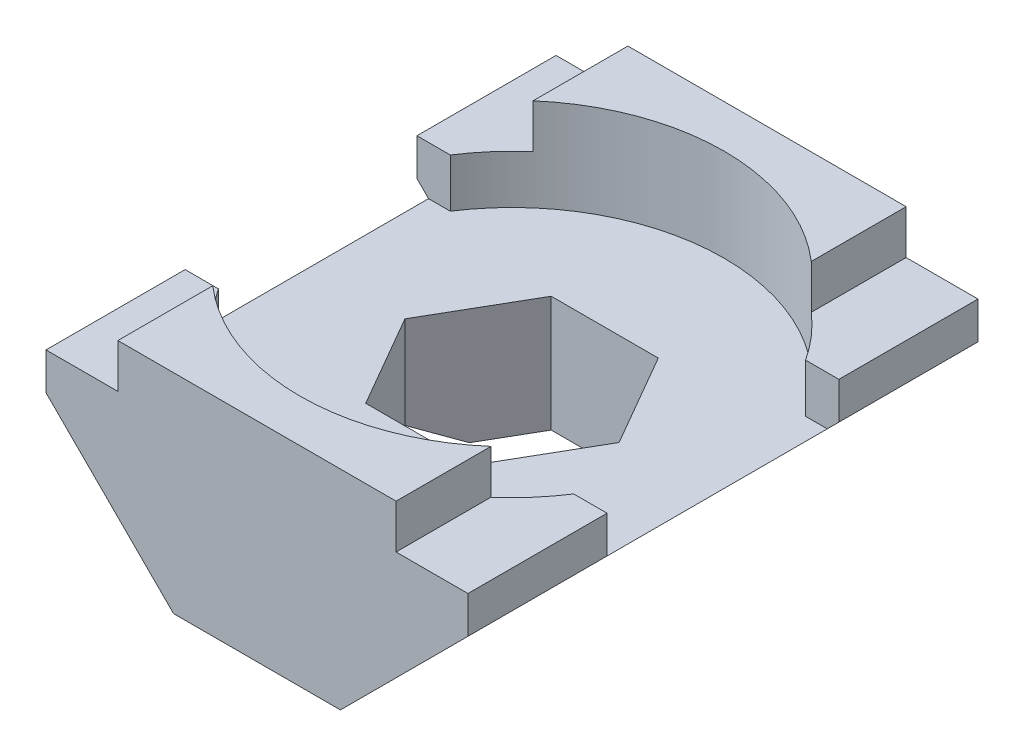
SolidWorks part; units mm, degrees
ref_plane "Front Plane" through (0, 0, 0) normal (0, 0, 1) x (1, 0, 0)
ref_plane "Top Plane" through (0, 0, 0) normal (0, 1, 0) x (1, 0, 0)
ref_plane "Right Plane" through (0, 0, 0) normal (1, 0, 0) x (0, 0, -1)
sketch "Sketch1" plane through (0, 0, 0) normal (0, 0, 1) x (1, 0, 0)
  line L0 (0, 0) -> (0, 5972.9771) construction
  line L1 (0, 0) -> (-5972.9771, 0) construction
  line L2 (0, 0) -> (0, 0.95)
  line L3 (0, 0.95) -> (6, 0.95)
  line L4 (6, 0.95) -> (6, 0)
  line L5 (6, 0) -> (7.55, 0)
  line L6 (7.55, 0) -> (7.55, -0.8)
  line L7 (7.55, -0.8) -> (4.8, -3.55)
  line L8 (4.8, -3.55) -> (1.2, -3.55)
  line L9 (1.2, -3.55) -> (-1.55, -0.8)
  line L10 (-1.55, -0.8) -> (-1.55, 0)
  line L11 (-1.55, 0) -> (0, 0)
  dimension "D1" = 0.95
  dimension "D2" = 1.55
  dimension "D3" = 1.55
  dimension "D4" = 6
  dimension "D5" = 0.8
  dimension "D6" = 0.8
  dimension "D7" = 135
  dimension "D8" = 135
  dimension "D9" = 4.5
extrude "Boss-Extrude1" add sketch "Sketch1" along normal blind 16
sketch "Sketch2" plane through (0, 0.95, 0) normal (0, 1, 0) x (1, 0, 0)
  line L0 (0, -8) -> (6, -8) construction
  line L1 (0, -16) -> (0, 0) construction
  line L2 (6, -16) -> (6, 0) construction
  circle A0 centre (3, -8) radius 4.575
  dimension "D1" = 9.15
extrude "Cut-Extrude1" cut sketch "Sketch2" against normal blind 2
sketch "Sketch3" plane through (0, -1.05, 0) normal (0, 1, 0) x (1, 0, 0)
  line L0 (3, -8) -> (5.3094, -8) construction
  line L1 (5.3094, -8) -> (4.1547, -6)
  line L2 (4.1547, -6) -> (1.8453, -6)
  line L3 (1.8453, -6) -> (0.6906, -8)
  line L4 (0.6906, -8) -> (1.8453, -10)
  line L5 (1.8453, -10) -> (4.1547, -10)
  line L6 (4.1547, -10) -> (5.3094, -8)
  circle A0 centre (3, -8) radius 2 construction
  dimension "D1" = 4
extrude "Cut-Extrude2" cut sketch "Sketch3" against normal through all
sketch "Sketch5" plane through (0, -1.05, 0) normal (0, 1, 0) x (1, 0, 0)
  line L0 (-1.55, -7.5224) -> (-1.55, 0) construction
  line L1 (-1.55, -5.5) -> (7.55, -5.5)
  line L2 (-1.55, -5.5) -> (-1.55, -10.5)
  line L3 (-1.55, -10.5) -> (7.55, -10.5)
  line L4 (7.55, -5.5) -> (7.55, -10.5)
  line L5 (7.55, -16) -> (7.55, -8.4776) construction
  line L6 (-1.55, -8) -> (3, -8) construction
  point P11 (3, -8)
  dimension "D1" = 5
extrude "Cut-Extrude4" cut sketch "Sketch5" along normal through all
sketch "Sketch6" plane through (0, 0.95, 0) normal (0, 1, 0) x (1, 0, 0)
  line L0 (7.55, -5.5) -> (7.55, 0) construction
  line L1 (-1.55, 0) -> (7.55, 0)
  line L2 (-1.55, 0) -> (-1.55, -2.5)
  line L3 (-1.55, -2.5) -> (7.55, -2.5)
  line L4 (7.55, 0) -> (7.55, -2.5)
  line L6 (-1.55, -16) -> (7.55, -16)
  line L7 (-1.55, -16) -> (-1.55, -13.5)
  line L8 (-1.55, -13.5) -> (7.55, -13.5)
  line L9 (7.55, -16) -> (7.55, -13.5)
  dimension "D1" = 2.5
  dimension "D2" = 2.5
extrude "Cut-Extrude5" cut sketch "Sketch6" against normal through all
